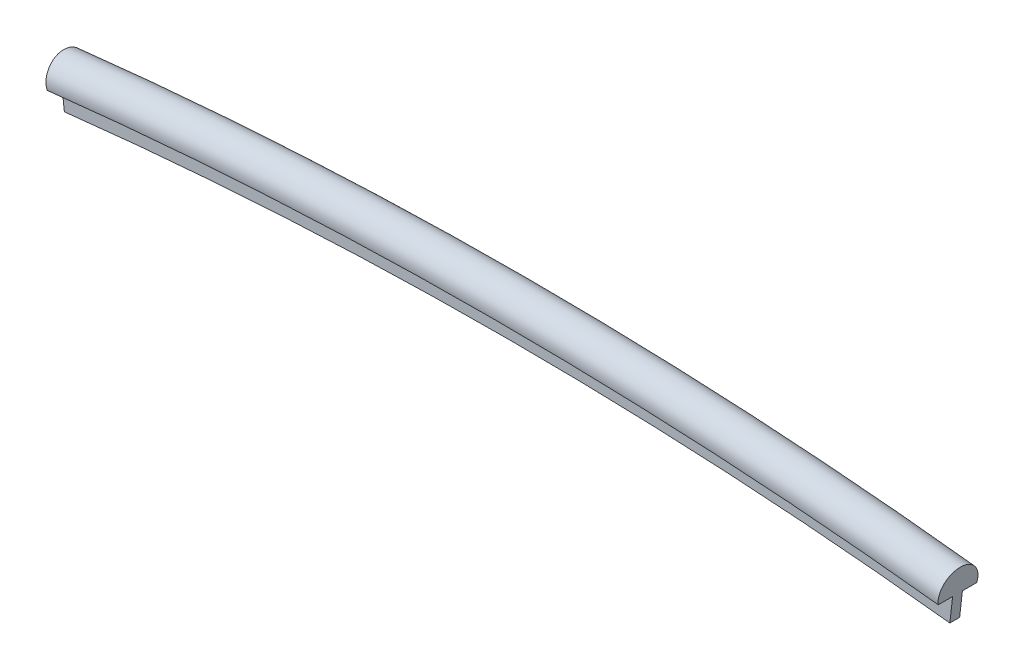
SolidWorks part; units mm, degrees
ref_plane "Front Plane" through (0, 0, 0) normal (0, 0, 1) x (1, 0, 0)
ref_plane "Top Plane" through (0, 0, 0) normal (0, 1, 0) x (1, 0, 0)
ref_plane "Right Plane" through (0, 0, 0) normal (1, 0, 0) x (0, 0, -1)
sketch "Sketch2" plane through (0, 0, 0) normal (1, 0, 0) x (0, 0, -1)
  line L0 (0, 241.3) -> (0, 0) construction
  line L2 (0, 241.3) -> (0, 239.8) construction
  line L3 (0, 239.8) -> (0.3, 239.8)
  line L4 (0, 239.8) -> (-0.3, 239.8)
  line L5 (-0.3, 239.8) -> (-0.3, 241.3)
  line L6 (0.3, 239.8) -> (0.3, 241.3)
  line L7 (0, 241.3) -> (0, 242.8) construction
  line L8 (-1.18, 241.3) -> (-0.3, 241.3)
  line L9 (0.3, 241.3) -> (1.18, 241.3)
  arc A0 (-1.18, 241.3) -> (1.18, 241.3) centre (0, 241.586) cw
  point P14 (0, 241.3)
ref_axis "Axis2" through (0, 0, 70.5976) along (0, 0, -1)
revolve "Revolve1" add sketch "Sketch2" angle 6.488 about axis through (0, 0, 70.5976) along (0, 0, -1)
